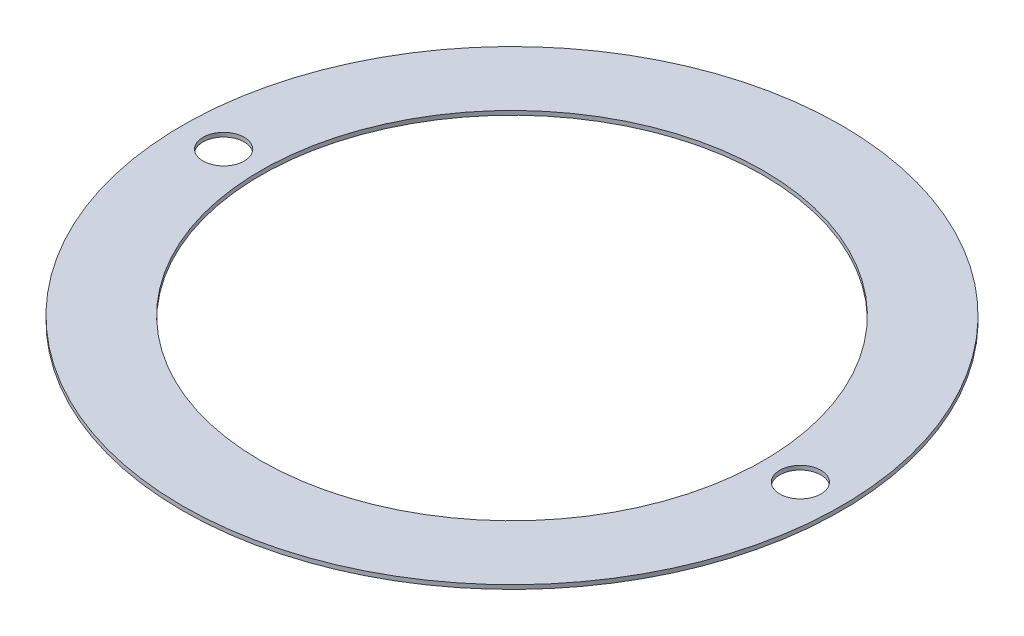
SolidWorks part; units mm, degrees
ref_plane "Front Plane" through (0, 0, 0) normal (0, 0, 1) x (1, 0, 0)
ref_plane "Top Plane" through (0, 0, 0) normal (0, 1, 0) x (1, 0, 0)
ref_plane "Right Plane" through (0, 0, 0) normal (1, 0, 0) x (0, 0, -1)
sketch "Sketch1" plane through (0, 0, 0) normal (0, 1, 0) x (1, 0, 0)
  circle A0 centre (0, 0) radius 8
  circle A1 centre (0, 0) radius 6.1
  dimension "D1" = 16
  dimension "D2" = 12.2
extrude "Boss-Extrude1" add sketch "Sketch1" along normal blind 0.1
hole_wizard "Ø1.0 (1) Diameter Hole1" positions "Sketch3" profile "Sketch4" hole size "Ø1.0" standard "DIN" end condition up to next
sketch "Sketch3" plane through (0, 0.1, 0) normal (0, 1, 0) x (1, 0, 0)
  circle A0 centre (0, 0) radius 7 construction
  point P5 (-7, 0)
  point P7 (7, 0)
  dimension "D1" = 14
sketch "Sketch4" plane through (-7, 0.1, 0) normal (1, 0, 0) x (0, 0, 1)
  line L0 (0, 0) -> (0, 0.1)
  line L1 (0, 0.1) -> (0.5, 0.1)
  line L2 (0.5, 0.1) -> (0.5, 0)
  line L5 (0.5, 0) -> (0, 0)
  line L11 (0, -6.35) -> (0, 107.95) construction
  dimension "Thru Hole Dia." = 1
  dimension "Thru Hole Depth" = 0.1
